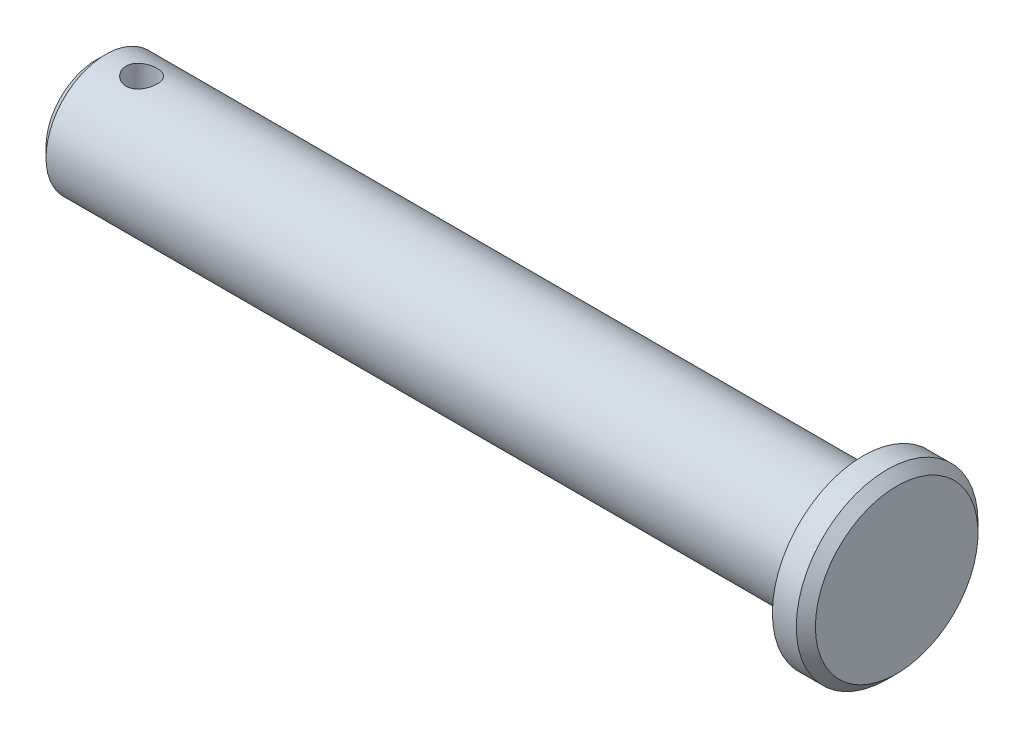
SolidWorks part; units mm, degrees
material "AISI 1045 Aço, trefilado"
ref_plane "Plano frontal" through (0, 0, 0) normal (0, 0, 1) x (1, 0, 0)
ref_plane "Plano superior" through (0, 0, 0) normal (0, 1, 0) x (1, 0, 0)
ref_plane "Plano direito" through (0, 0, 0) normal (1, 0, 0) x (0, 0, -1)
sketch "Esboço1" plane through (0, 0, 0) normal (0, 0, 1) x (1, 0, 0)
  line L0 (-83.69, 0) -> (83.69, 0) construction
  line L1 (83.69, 0) -> (83.69, 17)
  line L2 (81.69, 19) -> (76.69, 19)
  line L3 (76.69, 19) -> (76.69, 12.5)
  line L4 (76.69, 12.5) -> (-81.69, 12.5)
  line L5 (-83.69, 10.5) -> (-83.69, 0)
  line L6 (-81.69, 12.5) -> (-83.69, 10.5)
  line L7 (83.69, 17) -> (81.69, 19)
  line L8 (-83.69, 0) -> (83.69, 0)
  point P4 (83.69, 19)
  point P7 (-83.69, 12.5)
  point P12 (84.69, 0.4635)
  dimension "D1" = 38
  dimension "D2" = 25
  dimension "D3" = 167.38
  dimension "D4" = 7
revolve "Revolução1" add sketch "Esboço1" angle 360 about L0
sketch "Esboço2" plane through (0, 0, 0) normal (0, 1, 0) x (1, 0, 0)
  line L0 (-83.69, 0) -> (-74.19, 0) construction
  line L1 (-83.69, 10.5) -> (-83.69, -10.5) construction
  line L2 (-20.9, 0) -> (20.9, 0) construction
  circle A0 centre (-74.19, 0) radius 3.25
  dimension "D2" = 6.5
  dimension "D1" = 9.5
extrude "Corte-extrusão1" cut sketch "Esboço2" against normal through all both and the other way through all
